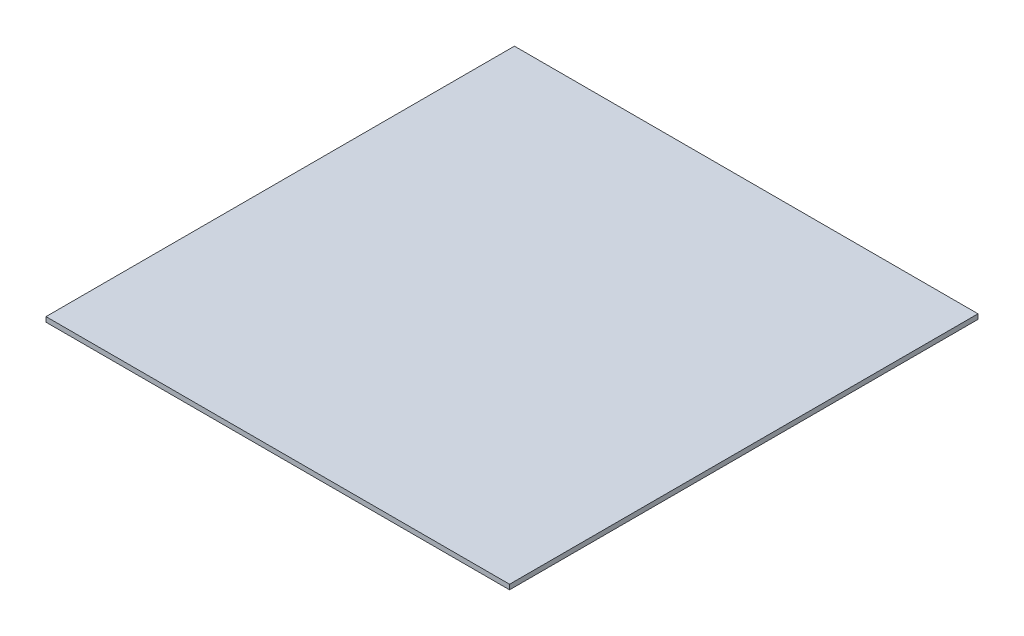
SolidWorks part; units mm, degrees
ref_plane "Front Plane" through (0, 0, 0) normal (0, 0, 1) x (1, 0, 0)
ref_plane "Top Plane" through (0, 0, 0) normal (0, 1, 0) x (1, 0, 0)
ref_plane "Right Plane" through (0, 0, 0) normal (1, 0, 0) x (0, 0, -1)
sketch "Sketch1" plane through (0, 0, 0) normal (0, 1, 0) x (1, 0, 0)
  line L1 (-22.1533, 275.6125) -> (279.4717, 275.6125)
  line L2 (-22.1533, 275.6125) -> (-22.1533, -29.1875)
  line L3 (-22.1533, -29.1875) -> (279.4717, -29.1875)
  line L4 (279.4717, 275.6125) -> (279.4717, -29.1875)
  dimension "D1" = 301.625
  dimension "D2" = 304.8
extrude "Boss-Extrude1" add sketch "Sketch1" along normal blind 3.175 contours L2 L1 L4 L3
